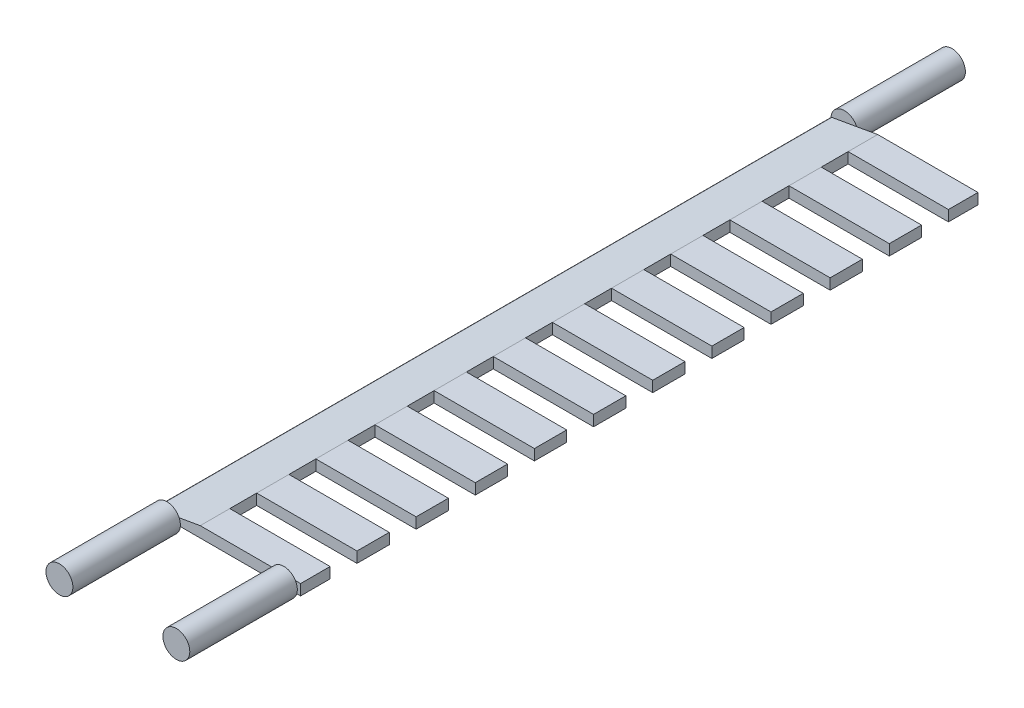
SolidWorks part; units mm, degrees
ref_plane "前视基准面" through (0, 0, 0) normal (0, 0, 1) x (1, 0, 0)
ref_plane "上视基准面" through (0, 0, 0) normal (0, 1, 0) x (1, 0, 0)
ref_plane "右视基准面" through (0, 0, 0) normal (1, 0, 0) x (0, 0, -1)
other "Configuration Table"
sketch "草图1" plane through (0, 0, 0) normal (0, 0, 1) x (1, 0, 0)
  line L3 (2.8575, 0) -> (30, 0)
  line L4 (30, 0) -> (30, 2)
  line L5 (30, 2) -> (11.3426, 2)
  line L6 (11.3426, 2) -> (2.8141, 0.4962)
  arc A0 (2.8141, 0.4962) -> (2.8575, 0) centre (2.8575, 0.25) ccw
  point P10 (0, 0)
  dimension "D4" = 0.25
  dimension "D1" = 2
  dimension "D2" = 30
  dimension "D3" = 170
extrude "凸台-拉伸1" add sketch "草图1" along normal mid plane 126
sketch "草图2" plane through (0, 2, 0) normal (0, 1, 0) x (1, 0, 0)
  line L0 (30, -63) -> (30, 63) construction
  line L1 (48.6574, -2.5) -> (11.3426, -2.5)
  line L2 (48.6574, -2.5) -> (48.6574, 2.5)
  line L3 (48.6574, 2.5) -> (11.3426, 2.5)
  line L4 (11.3426, -2.5) -> (11.3426, 2.5)
  line L5 (48.6574, -2.5) -> (11.3426, 2.5) construction
  line L6 (48.6574, 2.5) -> (11.3426, -2.5) construction
  line L7 (11.3426, -63) -> (11.3426, 63) construction
  point P0 (30, 0)
  dimension "D1" = 5
extrude "切除-拉伸1" cut sketch "草图2" against normal mid plane 100
pattern_linear "阵列(线性)1" count 6 spacing 11 along (0, 0, -1) of "切除-拉伸1"
mirror "镜向1" about plane through (0, 0, 0) normal (0, 0, 1) of "阵列(线性)1"
sketch "草图3" plane through (0, 0, 0) normal (0, 0, 1) x (1, 0, 0)
  circle A0 centre (5.1553, 0.2626) radius 2.5
  point P2 (5.1553, 0.2626)
  dimension "D1" = 5
extrude "凸台-拉伸2" add sketch "草图3" along normal blind 20 from offset 63
mirror "镜向2" about plane through (0, 0, 0) normal (0, 0, 1) of "凸台-拉伸2"
sketch "草图4" plane through (0, 0, 63) normal (0, 0, 1) x (1, 0, 0)
  circle A0 centre (26.9023, 0.725) radius 2.5
  dimension "D1" = 5
extrude "凸台-拉伸3" add sketch "草图4" along normal through all
